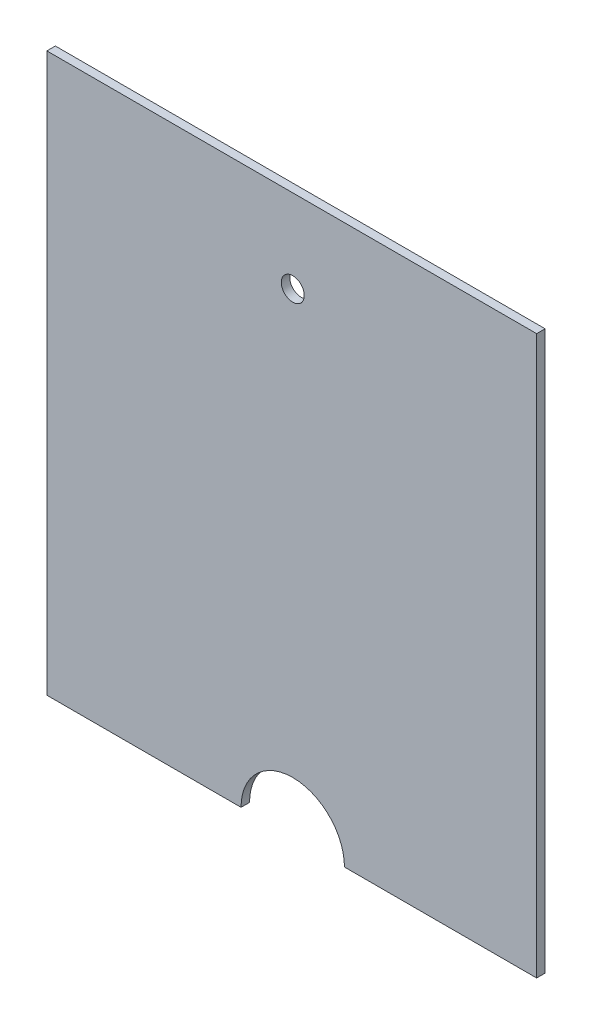
SolidWorks part; units mm, degrees
ref_plane "Front Plane" through (0, 0, 0) normal (0, 0, 1) x (1, 0, 0)
ref_plane "Top Plane" through (0, 0, 0) normal (0, 1, 0) x (1, 0, 0)
ref_plane "Right Plane" through (0, 0, 0) normal (1, 0, 0) x (0, 0, -1)
sketch "Sketch1" plane through (0, 0, 0) normal (0, 0, 1) x (1, 0, 0)
  line L2 (-135.1474, 81.5716) -> (-135.1474, -112.6984)
  line L3 (-135.1474, -112.6984) -> (-67.5526, -112.6984)
  line L4 (35.3526, 81.5716) -> (35.3526, -112.6984)
  line L5 (-31.5526, -112.6984) -> (35.3526, -112.6984)
  line L6 (-135.1474, 81.5716) -> (35.3526, 81.5716)
  arc A2 (-31.5526, -112.6984) -> (-67.5526, -112.6984) centre (-49.5526, -112.6984) ccw
  circle A3 centre (-49.5526, 52.6043) radius 4
  point P6 (-49.5526, 52.6043)
  dimension "D5" = 18
  dimension "D1" = 194.27
  dimension "D2" = 170.5
extrude "Boss-Extrude1" add sketch "Sketch1" along normal blind 2.95
equation "\"Width\"= 170.5"
equation "\"Height\"= 200 - 5.73"
equation "\"thin Acrylic\"= 2.95"
equation "\"D1@Sketch1\"=\"Height\""
equation "\"D2@Sketch1\"=\"Width\""
equation "\"D1@Boss-Extrude1\"=\"thin Acrylic\""
equation "\"Thick acrylic\"= 5.63"
equation "\"Drone height\"= 21.5"
equation "\"Guard height\"= \"Drone height\" - \"Thick acrylic\""
equation "\"Support width\"= 20"
equation "\"Wire Hole\"=18"
equation "\"D5@Sketch1\"=\"Wire Hole\""
